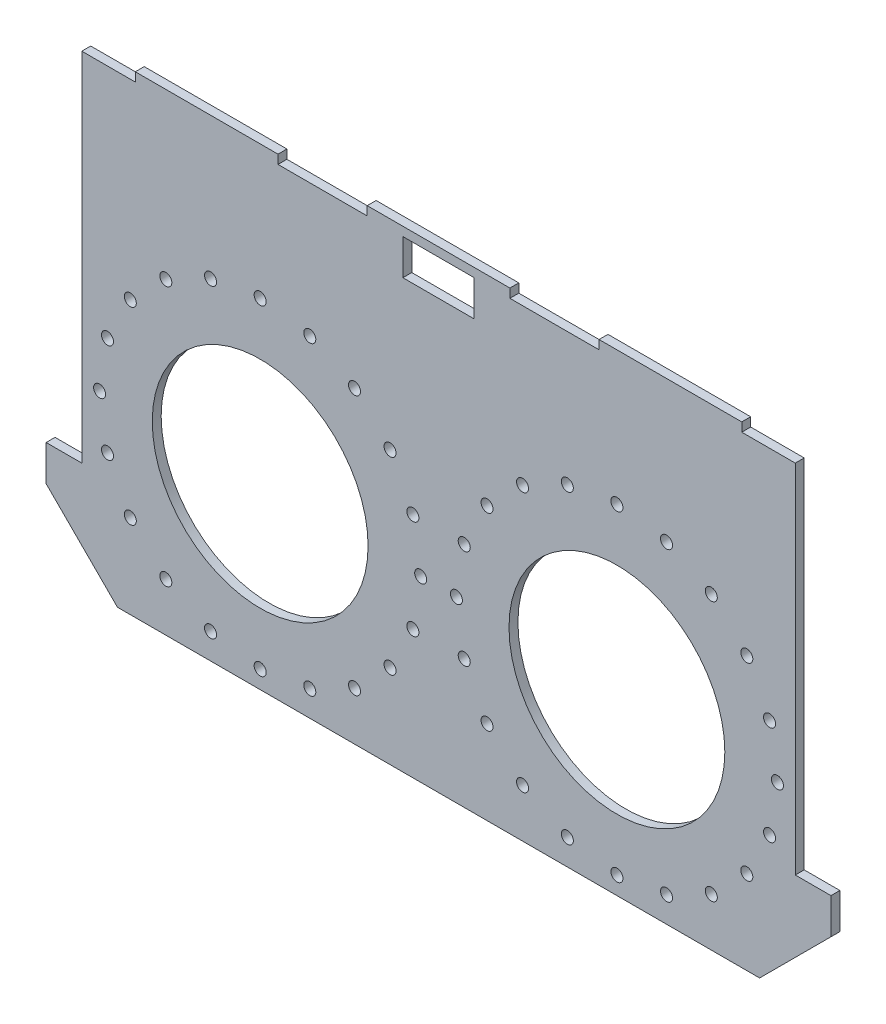
SolidWorks part; units mm, degrees
ref_plane "Plan de face" through (0, 0, 0) normal (0, 0, 1) x (1, 0, 0)
ref_plane "Plan de dessus" through (0, 0, 0) normal (0, 1, 0) x (1, 0, 0)
ref_plane "Plan de droite" through (0, 0, 0) normal (1, 0, 0) x (0, 0, -1)
sketch "Esquisse1" plane through (0, 0, 0) normal (0, 0, 1) x (1, 0, 0)
  line L0 (440, 530) -> (440, 0) construction
  line L1 (0, 0) -> (880, 0)
  line L2 (0, 0) -> (0, 530)
  line L3 (0, 530) -> (880, 530)
  line L4 (880, 0) -> (880, 530)
  line L5 (240, 200) -> (640, 200) construction
  line L6 (640, 200) -> (820, 200) construction
  line L7 (811.1902, 255.6231) -> (640, 200) construction
  line L8 (68.8098, 255.6231) -> (240, 200) construction
  line L9 (240, 200) -> (60, 200) construction
  circle A0 centre (640, 200) radius 121
  circle A1 centre (820, 200) radius 6.75
  circle A2 centre (640, 200) radius 180 construction
  circle A3 centre (811.1902, 144.3769) radius 6.75
  circle A4 centre (785.6231, 94.1987) radius 6.75
  circle A5 centre (745.8013, 54.3769) radius 6.75
  circle A6 centre (695.6231, 28.8098) radius 6.75
  circle A7 centre (640, 20) radius 6.75
  circle A8 centre (584.3769, 28.8098) radius 6.75
  circle A9 centre (534.1987, 54.3769) radius 6.75
  circle A10 centre (494.3769, 94.1987) radius 6.75
  circle A11 centre (468.8098, 144.3769) radius 6.75
  circle A12 centre (460, 200) radius 6.75
  circle A13 centre (468.8098, 255.6231) radius 6.75
  circle A14 centre (494.3769, 305.8013) radius 6.75
  circle A15 centre (534.1987, 345.6231) radius 6.75
  circle A16 centre (584.3769, 371.1902) radius 6.75
  circle A17 centre (640, 380) radius 6.75
  circle A18 centre (695.6231, 371.1902) radius 6.75
  circle A19 centre (745.8013, 345.6231) radius 6.75
  circle A20 centre (785.6231, 305.8013) radius 6.75
  circle A21 centre (811.1902, 255.6231) radius 6.75
  circle A22 centre (240, 200) radius 180 construction
  circle A23 centre (68.8098, 255.6231) radius 6.75
  circle A24 centre (94.3769, 305.8013) radius 6.75
  circle A25 centre (134.1987, 345.6231) radius 6.75
  circle A26 centre (184.3769, 371.1902) radius 6.75
  circle A27 centre (240, 380) radius 6.75
  circle A28 centre (295.6231, 371.1902) radius 6.75
  circle A29 centre (345.8013, 345.6231) radius 6.75
  circle A30 centre (385.6231, 305.8013) radius 6.75
  circle A31 centre (411.1902, 255.6231) radius 6.75
  circle A32 centre (420, 200) radius 6.75
  circle A33 centre (411.1902, 144.3769) radius 6.75
  circle A34 centre (385.6231, 94.1987) radius 6.75
  circle A35 centre (345.8013, 54.3769) radius 6.75
  circle A36 centre (295.6231, 28.8098) radius 6.75
  circle A37 centre (240, 20) radius 6.75
  circle A38 centre (184.3769, 28.8098) radius 6.75
  circle A39 centre (134.1987, 54.3769) radius 6.75
  circle A40 centre (94.3769, 94.1987) radius 6.75
  circle A41 centre (68.8098, 144.3769) radius 6.75
  circle A42 centre (60, 200) radius 6.75
  circle A43 centre (240, 200) radius 121
  point P54 (640, 200)
  point P56 (400, 280)
  dimension "D1" = 242
  dimension "D2" = 13.5
  dimension "D3" = 180
  dimension "D5" = 18
  dimension "D6" = 20
  dimension "D7" = 60
  dimension "D8" = 150
  dimension "D9" = 20
  dimension "D4" = 20
extrude "Boss.-Extru.1" add sketch "Esquisse1" along normal blind 10
chamfer "Chanfrein1" distance 80 angle 45 2 edges at (0, 0, 5) (880, 0, 5)
sketch "Esquisse2" plane through (0, 0, 0) normal (0, 0, -1) x (-1, 0, 0)
  line L0 (-440, 0) -> (-440, 530) construction
  line L1 (-880, 530) -> (-840, 530)
  line L2 (-880, 530) -> (-880, 120)
  line L3 (-880, 120) -> (-840, 120)
  line L4 (-840, 520) -> (-840, 120)
  line L5 (-80, 0) -> (-800, 0) construction
  line L6 (-880, 530) -> (0, 530) construction
  line L7 (-840, 120) -> (-440, 120) construction
  line L8 (-780, 520) -> (-620, 520) construction
  line L9 (-840, 530) -> (-780, 530)
  line L10 (-840, 530) -> (-840, 520) construction
  line L11 (-840, 520) -> (-780, 520)
  line L12 (-780, 530) -> (-780, 520)
  line L13 (-620, 530) -> (-520, 530)
  line L14 (-620, 530) -> (-620, 520)
  line L15 (-620, 520) -> (-520, 520)
  line L16 (-520, 530) -> (-520, 520)
  line L17 (-360, 520) -> (-520, 520) construction
  line L18 (-40, 530) -> (-40, 520) construction
  line L19 (-100, 520) -> (-260, 520) construction
  line L20 (-360, 530) -> (-360, 520)
  line L21 (-260, 520) -> (-360, 520)
  line L22 (-260, 530) -> (-260, 520)
  line L23 (-260, 530) -> (-360, 530)
  line L24 (-100, 530) -> (-100, 520)
  line L25 (-40, 520) -> (-100, 520)
  line L26 (-40, 530) -> (-100, 530)
  line L27 (-40, 520) -> (-40, 120)
  line L28 (0, 120) -> (-40, 120)
  line L29 (0, 530) -> (0, 120)
  line L30 (0, 530) -> (-40, 530)
  line L32 (-480, 520) -> (-400, 520)
  line L33 (-480, 520) -> (-480, 480)
  line L34 (-480, 480) -> (-400, 480)
  line L35 (-400, 520) -> (-400, 480)
  point P21 (-440, 520)
  point P35 (-440, 520)
  dimension "D1" = 40
  dimension "D2" = 410
  dimension "D3" = 80
  dimension "D4" = 100
  dimension "D5" = 160
  dimension "D6" = 10
  dimension "D7" = 80
  dimension "D8" = 40
extrude "Enlèv. mat.-Extru.1" cut sketch "Esquisse2" against normal blind 10
